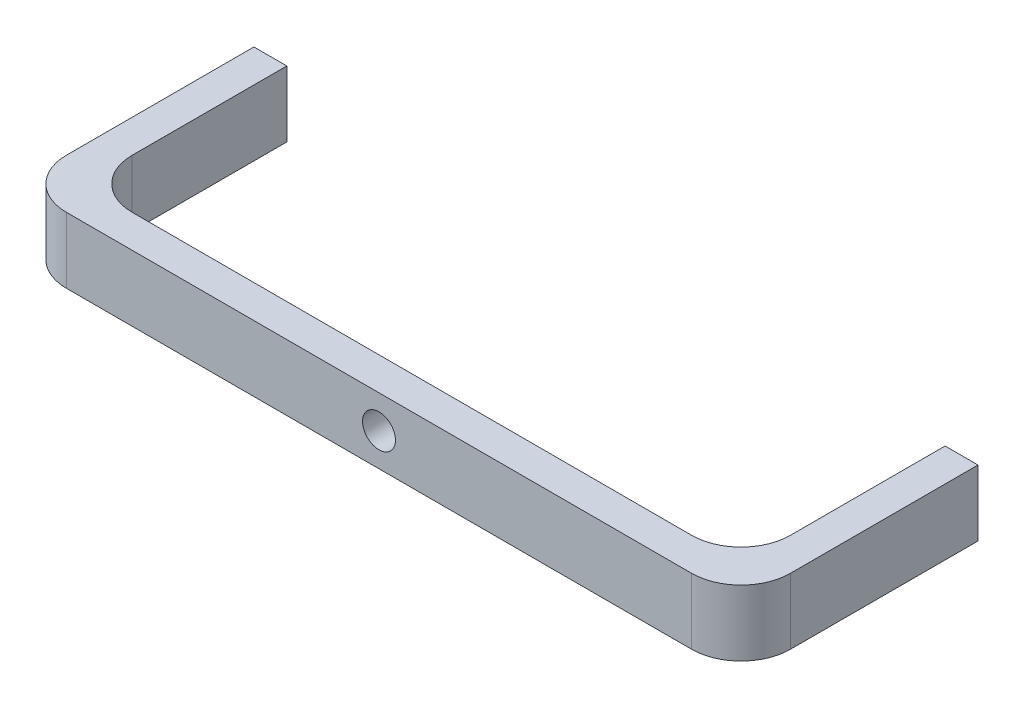
SolidWorks part; units mm, degrees
ref_plane "Front Plane" through (0, 0, 0) normal (0, 0, 1) x (1, 0, 0)
ref_plane "Top Plane" through (0, 0, 0) normal (0, 1, 0) x (1, 0, 0)
ref_plane "Right Plane" through (0, 0, 0) normal (1, 0, 0) x (0, 0, -1)
sketch "Sketch1" plane through (0, 0, 0) normal (0, 1, 0) x (1, 0, 0)
  line L0 (0, 0) -> (0, 101.7648) construction
  line L1 (-127, 6.35) -> (127, 6.35)
  line L3 (-127, -6.35) -> (127, -6.35)
  line L5 (-127, 6.35) -> (127, -6.35) construction
  line L6 (-127, -6.35) -> (127, 6.35) construction
  line L7 (-127, -6.35) -> (-139.7, -6.35)
  line L8 (-127, 6.35) -> (-127, 85.09)
  line L9 (-127, 85.09) -> (-139.7, 85.09)
  line L10 (-139.7, -6.35) -> (-139.7, 85.09)
  line L11 (127, 85.09) -> (139.7, 85.09)
  line L12 (139.7, -6.35) -> (139.7, 85.09)
  line L13 (127, -6.35) -> (139.7, -6.35)
  line L14 (127, 6.35) -> (127, 85.09)
  point P0 (0, 0)
  dimension "D1" = 12.7
  dimension "D2" = 254
  dimension "D3" = 78.74
  dimension "D4" = 12.7
extrude "Boss-Extrude1" add sketch "Sketch1" along normal blind 25.4
sketch "Sketch2" plane through (0, 0, 6.35) normal (0, 0, 1) x (1, 0, 0)
  line L0 (0, 0) -> (0, 25.4) construction
  line L1 (-139.7, 0) -> (139.7, 0) construction
  line L2 (-139.7, 25.4) -> (139.7, 25.4) construction
  circle A0 centre (0, 12.7) radius 6.35
  dimension "D1" = 12.7
extrude "Cut-Extrude1" cut sketch "Sketch2" against normal through all
fillet "Fillet1" radius 19.05 4 edges at (127, 12.7, -6.35) (139.7, 12.7, 6.35) (-127, 12.7, -6.35) (-139.7, 12.7, 6.35)
